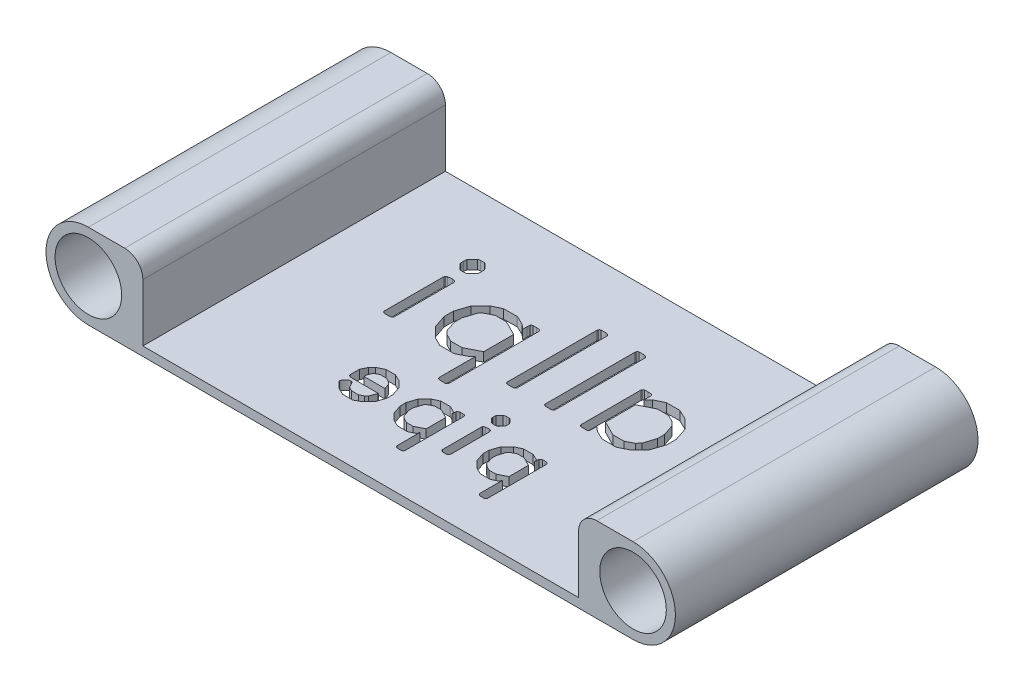
SolidWorks part; units mm, degrees
ref_plane "Front Plane" through (0, 0, 0) normal (0, 0, 1) x (1, 0, 0)
ref_plane "Top Plane" through (0, 0, 0) normal (0, 1, 0) x (1, 0, 0)
ref_plane "Right Plane" through (0, 0, 0) normal (1, 0, 0) x (0, 0, -1)
sketch "Sketch1" plane through (0, 0, 0) normal (0, 0, 1) x (1, 0, 0)
  line L0 (0, 0) -> (180, 0) construction
  line L1 (180, -14) -> (0, -14)
  line L2 (0, 14) -> (12, 14)
  line L3 (25, -11) -> (155, -11)
  line L4 (18, 8) -> (18, -5)
  line L5 (180, 14) -> (168, 14)
  line L6 (162, 8) -> (162, -5)
  line L7 (156, -11) -> (155, -11)
  line L8 (24, -11) -> (25, -11)
  line L9 (24, -11) -> (18, -11)
  line L10 (18, -11) -> (18, -5)
  line L11 (156, -11) -> (162, -11)
  line L12 (162, -11) -> (162, -5)
  circle A0 centre (0, 0) radius 11
  circle A1 centre (180, 0) radius 11
  arc A2 (0, 14) -> (0, -14) centre (0, 0) ccw
  arc A3 (180, -14) -> (180, 14) centre (180, 0) ccw
  arc A4 (12, 14) -> (18, 8) centre (12, 8) cw
  arc A6 (168, 14) -> (162, 8) centre (168, 8) ccw
  point P19 (18, -11)
  point P22 (162, 14)
  dimension "D1" = 22
  dimension "D2" = 22
  dimension "D4" = 28
  dimension "D9" = 6
  dimension "D3" = 180
  dimension "D5" = 3
  dimension "D6" = 130
  dimension "D7" = 18
  dimension "D8" = 18
extrude "Boss-Extrude1" add sketch "Sketch1" along normal blind 100
sketch "Sketch3" plane through (0, -14, 0) normal (0, -1, 0) x (-1, 0, 0)
  line L0 (-180, -50) -> (0, -50) construction
  line L1 (-180, -100) -> (-180, 0) construction
  line L2 (0, -100) -> (0, 0) construction
  text T0 "allpi\r\n" font "SWRomnd" height in points 120
extrude "Cut-Extrude1" cut sketch "Sketch3" against normal blind 10
sketch "Sketch4" plane through (0, -14, 0) normal (0, -1, 0) x (1, 0, 0)
  line L0 (180, 80.2992) -> (0, 80.2992) construction
  line L1 (180, 100) -> (180, 0) construction
  line L2 (0, 100) -> (0, 0) construction
  text T0 "pipe" font "SWRomnd" height in points 80
extrude "Cut-Extrude2" cut sketch "Sketch4" against normal blind 10
